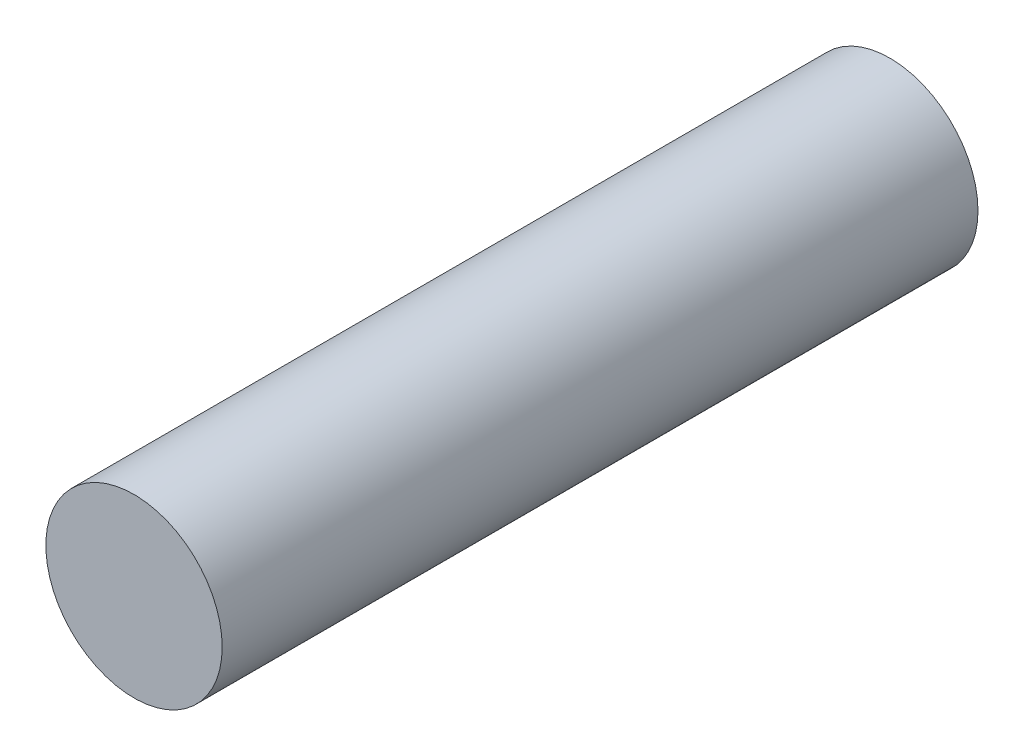
SolidWorks part; units mm, degrees
ref_plane "Front Plane" through (0, 0, 0) normal (0, 0, 1) x (1, 0, 0)
ref_plane "Top Plane" through (0, 0, 0) normal (0, 1, 0) x (1, 0, 0)
ref_plane "Right Plane" through (0, 0, 0) normal (1, 0, 0) x (0, 0, -1)
sketch "Sketch1" plane through (0, 0, 0) normal (0, 0, 1) x (1, 0, 0)
  line L0 (0, 52.3721) -> (0, -60.5678) construction
  line L1 (-101.8252, 0) -> (102.434, 0) construction
  circle A1 centre (0, 0) radius 3.5
extrude "Boss-Extrude1" add sketch "Sketch1" along normal blind 30
